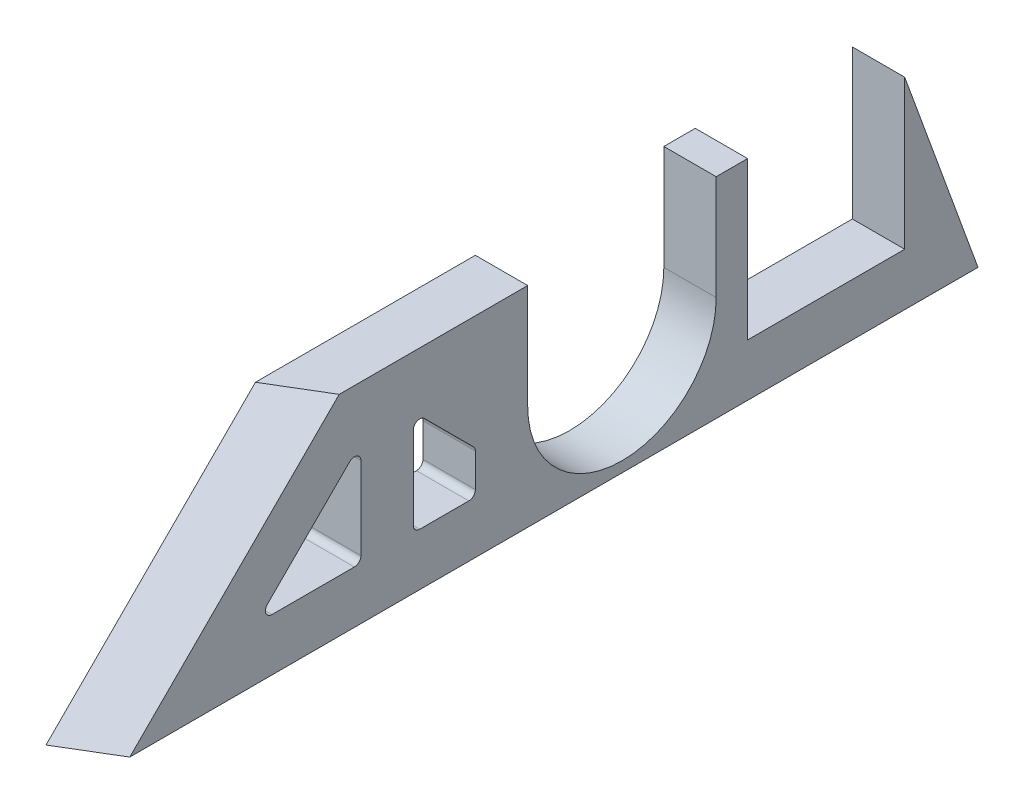
SolidWorks part; units mm, degrees
material "PE High Density"
ref_plane "Front Plane" through (0, 0, 0) normal (0, 0, 1) x (1, 0, 0)
ref_plane "Top Plane" through (0, 0, 0) normal (0, 1, 0) x (1, 0, 0)
ref_plane "Right Plane" through (0, 0, 0) normal (1, 0, 0) x (0, 0, -1)
sketch "Sketch1" plane through (0, 0, 0) normal (1, 0, 0) x (0, 0, -1)
  line L0 (-106.68, 0) -> (106.68, 0)
  line L1 (106.68, 0) -> (88.9, 48.8501)
  line L2 (88.9, 48.8501) -> (88.9, 12.7)
  line L3 (88.9, 12.7) -> (50.8, 12.7)
  line L4 (50.8, 12.7) -> (50.8, 50.8)
  line L5 (50.8, 50.8) -> (-55.88, 50.8)
  line L6 (-55.88, 50.8) -> (-106.68, 0)
  line L7 (-2.54, 25.4) -> (-2.54, 50.8)
  line L8 (43.18, 25.4) -> (43.18, 50.8)
  circle A0 centre (20.32, 25.4) radius 22.86
  dimension "D8" = 45.72
  dimension "D1" = 213.36
  dimension "D2" = 45
  dimension "D3" = 50.8
  dimension "D4" = 12.7
  dimension "D5" = 38.1
  dimension "D6" = 17.78
  dimension "D7" = 70
  dimension "D9" = 25.4
  dimension "D10" = 86.36
extrude "Boss-Extrude1" add sketch "Sketch1" along normal blind 12.7 contours A0 L7 L5 L6 L0 L1 L2 L3 L4 L8
sketch "Sketch2" plane through (0, 0, 0) normal (0, -1, 0) x (1, 0, 0)
  line L0 (0, 106.68) -> (12.7, 106.68)
  line L1 (12.7, 106.68) -> (12.7, 99.06)
  line L2 (12.7, 106.68) -> (12.7, -106.68) construction
  line L3 (12.7, 99.06) -> (0, 106.68)
  dimension "D1" = 7.62
extrude "Cut-Extrude1" cut sketch "Sketch2" along direction (0, -0.7071, 0.7071) on the side against the normal up to next (50.8 mm away)
sketch "Sketch3" plane through (12.7, 0, 0) normal (1, 0, 0) x (0, 0, -1)
  line L0 (-68.3995, 12.7) -> (-42.9995, 38.1)
  line L1 (-42.9995, 38.1) -> (-42.9995, 12.7)
  line L2 (-42.9995, 12.7) -> (-68.3995, 12.7)
  line L3 (-30.2995, 38.1) -> (-30.2995, 12.7)
  line L4 (-30.2995, 12.7) -> (-4.8995, 12.7)
  line L5 (-4.8995, 12.7) -> (-30.2995, 38.1)
  line L9 (-48.26, 50.8) -> (-99.06, 0) construction
  line L10 (-99.06, 0) -> (106.68, 0) construction
  line L13 (-2.54, 50.8) -> (-48.26, 50.8) construction
  line L14 (-15.24, 23.0405) -> (-15.24, 12.7)
  line L15 (-2.54, 25.4) -> (-2.54, 50.8) construction
  dimension "D1" = 12.7
  dimension "D2" = 12.7
  dimension "D3" = 12.7
  dimension "D4" = 12.7
  dimension "D5" = 12.7
extrude "Cut-Extrude2" cut sketch "Sketch3" against normal up to next contours L2 L1 L0 | L14 L5 L3 L4
fillet "Fillet1" radius 1.5875 7 edges at (6.35, 12.7, 68.3995) (6.35, 12.7, 30.2995) (6.35, 12.7, 42.9995) (6.35, 12.7, 15.24) (6.35, 38.1, 42.9995) (6.35, 38.1, 30.2995) (6.35, 23.0405, 15.24)
